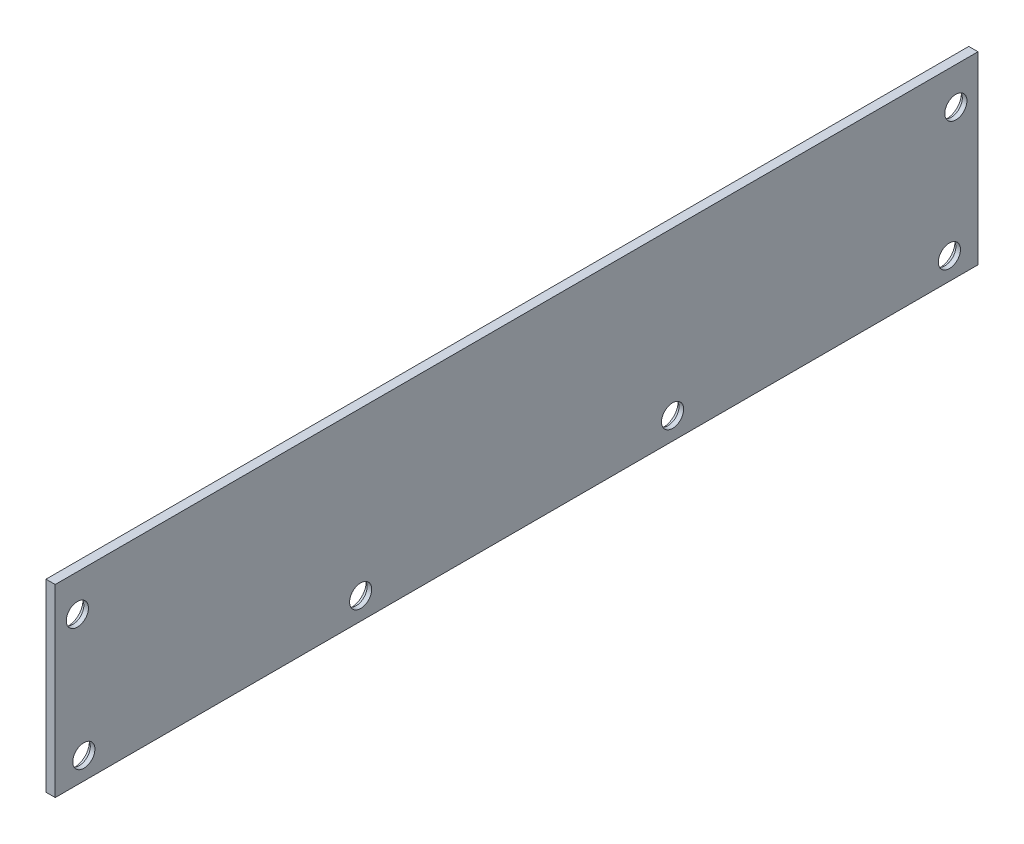
SolidWorks part; units mm, degrees
ref_plane "Front Plane" through (0, 0, 0) normal (0, 0, 1) x (1, 0, 0)
ref_plane "Top Plane" through (0, 0, 0) normal (0, 1, 0) x (1, 0, 0)
ref_plane "Right Plane" through (0, 0, 0) normal (1, 0, 0) x (0, 0, -1)
sketch "Sketch1" plane through (0, 0, 0) normal (1, 0, 0) x (0, -1, 0)
  line L0 (0, -152.4) -> (0, 152.4) construction
  line L1 (25.4, 152.4) -> (25.4, -152.4)
  line L2 (25.4, 152.4) -> (-25.4, 152.4)
  line L3 (-25.4, 152.4) -> (-25.4, -152.4)
  line L4 (25.4, -152.4) -> (-25.4, -152.4)
  line L5 (25.4, 152.4) -> (-25.4, -152.4) construction
  line L6 (-25.4, 152.4) -> (25.4, -152.4) construction
  line L7 (-25.4, 0) -> (25.4, 0) construction
  point P0 (0, 0)
  point P10 (0, 101.6)
  point P11 (0, -101.6)
  dimension "Length" = 304.8
  dimension "Width" = 50.8
  dimension "D1" = 50.8
sketch "Sketch2" plane through (0, 0, 0) normal (0, 0, -1) x (-1, 0, 0)
  line L0 (-0.635, 25.4) -> (0.635, 25.4) construction
  point P2 (0, 25.4)
  dimension "Thickness" = 1.27
sketch "Sketch3" plane through (0, 0, 0) normal (0, 0, 1) x (1, 0, 0)
  line L5 (-0.635, 0) -> (0.635, 0)
  line L6 (-0.635, 0) -> (-0.635, -25.4)
  line L7 (-0.635, -25.4) -> (0.635, -25.4)
  line L8 (0.635, 0) -> (0.635, -25.4)
extrude "Boss-Extrude1" add sketch "Sketch3" against normal blind 127
sketch "Sketch5" plane through (-0.635, 0, 0) normal (-1, 0, 0) x (0, 0, 1)
  line L0 (-127, 0) -> (-127, -25.4) construction
  line L6 (-127, 0) -> (0, 0) construction
  line L7 (-127, -25.4) -> (0, -25.4) construction
  line L8 (0, 0) -> (0, -25.4) construction
  circle A0 centre (-123.063, -22.352) radius 1.524
  circle A1 centre (-84.963, -22.352) radius 1.524
  circle A2 centre (-123.952, -5.08) radius 1.524
  circle A3 centre (-42.037, -22.352) radius 1.524
  circle A4 centre (-3.937, -22.352) radius 1.524
  circle A5 centre (-3.048, -5.08) radius 1.524
  point P18 (-86.3152, -22.352)
  point P19 (0, 0)
  point P20 (-40.5653, -22.352)
  point P21 (-2.914, -22.352)
  dimension "D2" = 5.08
  dimension "D1" = 3.048
  dimension "D3" = 3.937
  dimension "D4" = 3.048
  dimension "D5" = 38.1
  dimension "D6" = 38.1
  dimension "D7" = 3.937
  dimension "D8" = 3.048
  dimension "D9" = 3.048
  dimension "D10" = 5.08
extrude "Cut-Extrude1" cut sketch "Sketch5" against normal blind 1.27
sketch "Sketch6" plane through (-0.635, 0, 0) normal (-1, 0, 0) x (0, 0, 1)
  circle A0 centre (-123.952, -5.08) radius 2.032
  circle A1 centre (-123.063, -22.352) radius 2.032
  circle A2 centre (-84.963, -22.352) radius 2.032
  circle A3 centre (-42.037, -22.352) radius 2.032
  circle A4 centre (-3.937, -22.352) radius 2.032
  circle A6 centre (-3.048, -5.08) radius 2.032
  circle M1 centre (-84.963, -22.352) radius 1.524
  circle M3 centre (-42.037, -22.352) radius 1.524
  circle M4 centre (-3.937, -22.352) radius 1.524
  circle M5 centre (-3.048, -5.08) radius 1.524
  circle M6 centre (-123.063, -22.352) radius 1.524
extrude "Cut-Extrude3" cut sketch "Sketch6" against normal blind 0.635 contours A1 M6 | A2 M1 | A3 M3 | A4 M4 | A6 M5 | A0
equation "\"D1@Sketch1\"=\"Width@Sketch1\"*1"
equation "\"D1@Fillet1\"=\"Thickness@Sketch2\" * .033"
